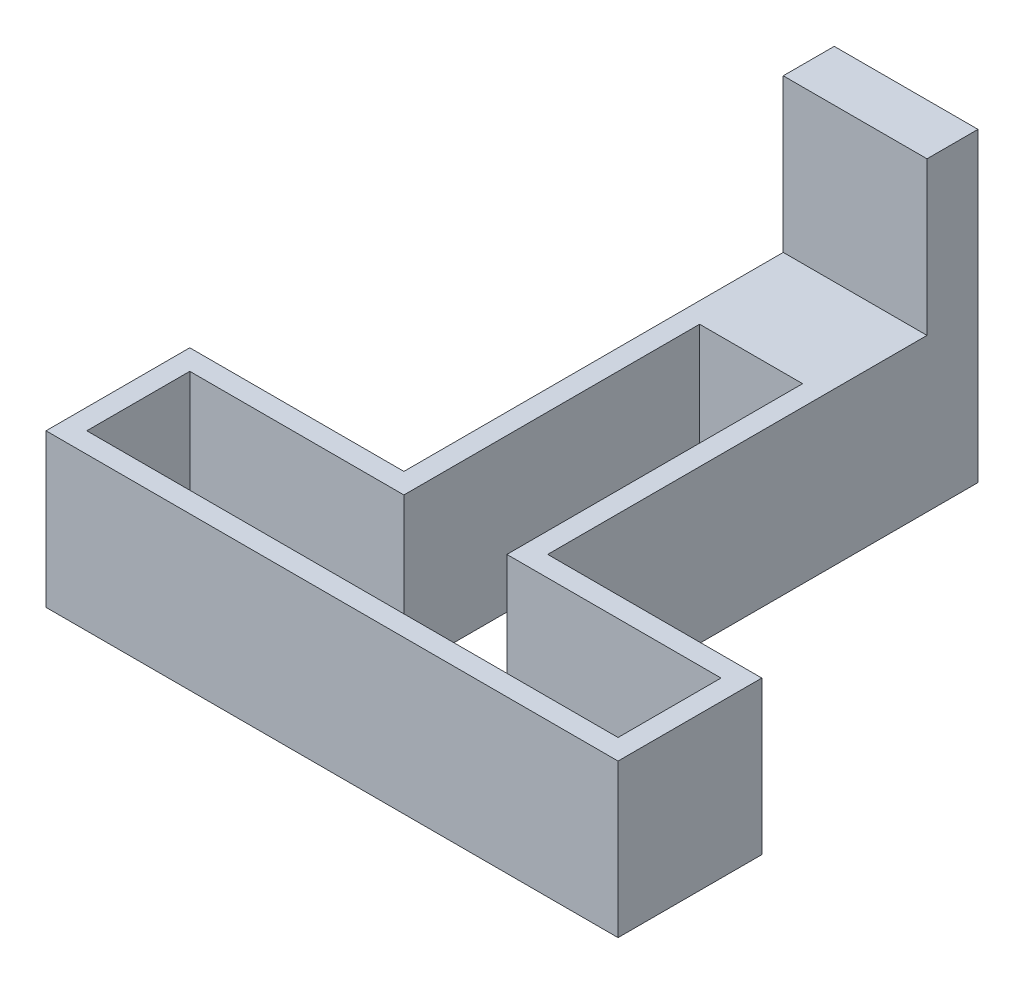
SolidWorks part; units mm, degrees
ref_plane "Ebene vorne" through (0, 0, 0) normal (0, 0, 1) x (1, 0, 0)
ref_plane "Ebene oben" through (0, 0, 0) normal (0, 1, 0) x (1, 0, 0)
ref_plane "Ebene rechts" through (0, 0, 0) normal (1, 0, 0) x (0, 0, -1)
sketch "Skizze1" plane through (0, 0, 0) normal (0, 1, 0) x (1, 0, 0)
  line L0 (0, 0) -> (52.1, 0)
  line L1 (52.1, 0) -> (52.1, 10.1)
  line L2 (52.1, 10.1) -> (31.1, 10.1)
  line L3 (31.1, 10.1) -> (31.1, 52.3)
  line L4 (31.1, 52.3) -> (21, 52.3)
  line L5 (21, 52.3) -> (21, 10.1)
  line L6 (21, 10.1) -> (0, 10.1)
  line L7 (0, 10.1) -> (0, 0)
  line L8 (-2, 12.1) -> (-2, -2)
  line L9 (-2, -2) -> (54.1, -2)
  line L10 (54.1, -2) -> (54.1, 12.1)
  line L11 (54.1, 12.1) -> (33.1, 12.1)
  line L12 (33.1, 12.1) -> (33.1, 54.3)
  line L13 (33.1, 54.3) -> (19, 54.3)
  line L14 (19, 54.3) -> (19, 12.1)
  line L15 (19, 12.1) -> (-2, 12.1)
  dimension "D1" = 52.1
  dimension "D2" = 10.1
  dimension "D3" = 10.1
  dimension "D4" = 42.2
  dimension "D5" = 2
extrude "Aufsatz-Linear austragen1" add sketch "Skizze1" along normal blind 15
sketch "Skizze2" plane through (0, 15, 0) normal (0, 1, 0) x (1, 0, 0)
  line L0 (33.1, 12.1) -> (33.1, 54.3) construction
  line L1 (19, 54.3) -> (33.1, 54.3)
  line L2 (19, 54.3) -> (19, 49.3)
  line L3 (19, 49.3) -> (33.1, 49.3)
  line L4 (33.1, 54.3) -> (33.1, 49.3)
  line L5 (19, 54.3) -> (33.1, 49.3) construction
  line L6 (19, 49.3) -> (33.1, 54.3) construction
  line L7 (21, 10.1) -> (0, 10.1) construction
  point P4 (26.05, 51.8)
  dimension "D1" = 39.2
extrude "Aufsatz-Linear austragen2" add sketch "Skizze2" along normal blind 15
sketch "Skizze3" plane through (0, 0, 0) normal (0, -1, 0) x (1, 0, 0)
  line L0 (33.1, -12.1) -> (33.1, -54.3) construction
  line L1 (19, -54.3) -> (33.1, -54.3)
  line L2 (19, -54.3) -> (19, -39.1)
  line L3 (19, -39.1) -> (33.1, -39.1)
  line L4 (33.1, -54.3) -> (33.1, -39.1)
  line L5 (19, -54.3) -> (33.1, -39.1) construction
  line L6 (19, -39.1) -> (33.1, -54.3) construction
  line L7 (21, -10.1) -> (0, -10.1) construction
  point P4 (26.05, -46.7)
  dimension "D1" = 29
extrude "Aufsatz-Linear austragen3" add sketch "Skizze3" against normal up to surface (15 mm away) up to face at (26.05, 15, -17.625)
